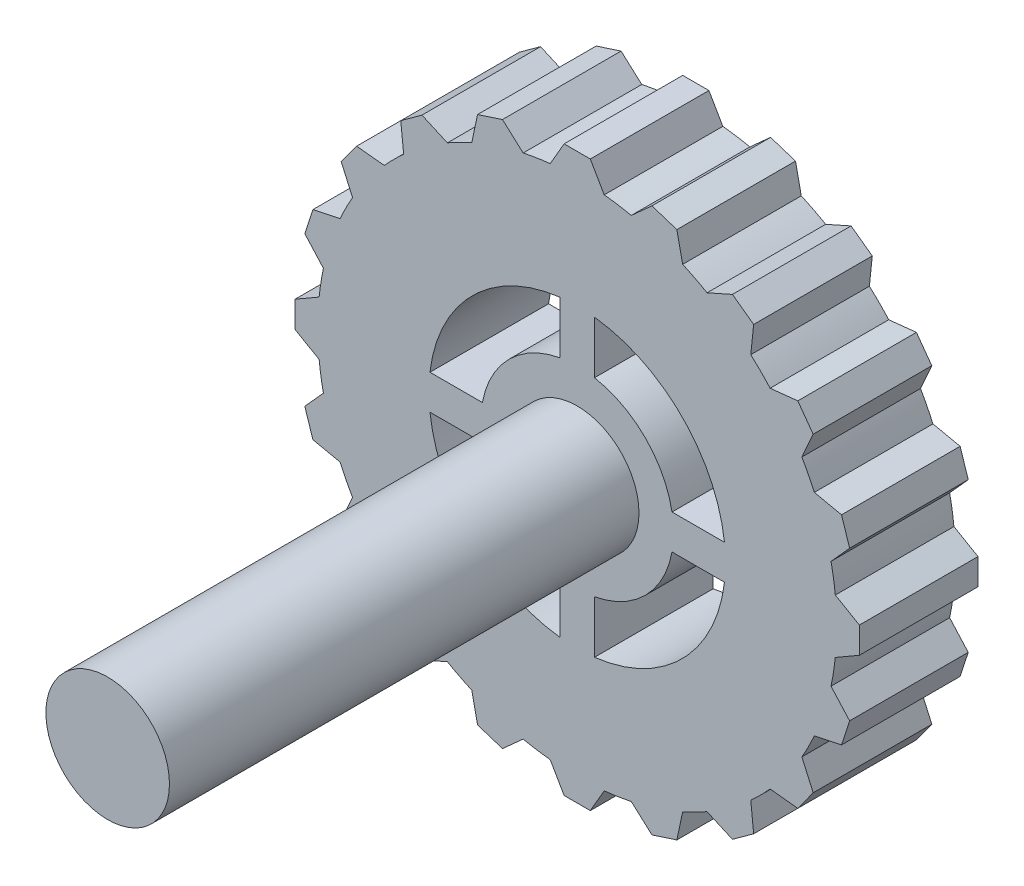
SolidWorks part; units mm, degrees
ref_plane "Płaszczyzna przednia" through (0, 0, 0) normal (0, 0, 1) x (1, 0, 0)
ref_plane "Płaszczyzna górna" through (0, 0, 0) normal (0, 1, 0) x (1, 0, 0)
ref_plane "Płaszczyzna prawa" through (0, 0, 0) normal (1, 0, 0) x (0, 0, -1)
sketch "Szkic1" plane through (0, 0, 0) normal (0, 0, 1) x (1, 0, 0)
  line L0 (0, 0) -> (0, 1.25) construction
  line L1 (0, 0) -> (-4.6726, 0) construction
  line L8 (-2.9795, 0.35) -> (-1.9183, 0.35)
  line L9 (-2.9795, -0.35) -> (-1.9183, -0.35)
  line L10 (-0.35, 2.9795) -> (-0.35, 1.9183)
  line L11 (0.35, 2.9795) -> (0.35, 1.9183)
  line L12 (1.9183, 0.35) -> (2.9795, 0.35)
  line L13 (1.9183, -0.35) -> (2.9795, -0.35)
  line L14 (-0.35, -1.9183) -> (-0.35, -2.9795)
  line L15 (0.35, -2.9795) -> (0.35, -1.9183)
  line L16 (0, 2.8529) -> (0, 9.5556) construction
  line L17 (1.5121, 5.5115) -> (1.0938, 5.1348)
  line L18 (-0.265, 5.709) -> (-0.5465, 5.2215)
  line L22 (0.5465, 5.2215) -> (0.265, 5.709)
  line L23 (0.265, 5.709) -> (-0.265, 5.709)
  line L24 (0, 4.791) -> (0.265, 4.791) [skipped]
  line L25 (0.5154, 5.2246) -> (0.53, 5.25) [skipped]
  line L26 (-0.53, 5.25) -> (-0.5154, 5.2246) [skipped]
  line L27 (2.1332, 4.7971) -> (2.0162, 5.3477)
  line L28 (2.0162, 5.3477) -> (1.5121, 5.5115)
  line L29 (3.1413, 4.7744) -> (2.627, 4.5455)
  line L30 (3.5112, 3.9031) -> (3.5701, 4.4629)
  line L31 (3.5701, 4.4629) -> (3.1413, 4.7744)
  line L32 (4.4629, 3.5701) -> (3.9031, 3.5112)
  line L33 (4.5455, 2.627) -> (4.7744, 3.1413)
  line L34 (4.7744, 3.1413) -> (4.4629, 3.5701)
  line L35 (5.3477, 2.0162) -> (4.7971, 2.1332)
  line L36 (5.1348, 1.0938) -> (5.5115, 1.5121)
  line L37 (5.5115, 1.5121) -> (5.3477, 2.0162)
  line L38 (5.709, 0.265) -> (5.2215, 0.5465)
  line L39 (5.2215, -0.5465) -> (5.709, -0.265)
  line L40 (5.709, -0.265) -> (5.709, 0.265)
  line L41 (5.5115, -1.5121) -> (5.1348, -1.0938)
  line L42 (4.7971, -2.1332) -> (5.3477, -2.0162)
  line L43 (5.3477, -2.0162) -> (5.5115, -1.5121)
  line L44 (4.7744, -3.1413) -> (4.5455, -2.627)
  line L45 (3.9031, -3.5112) -> (4.4629, -3.5701)
  line L46 (4.4629, -3.5701) -> (4.7744, -3.1413)
  line L47 (3.5701, -4.4629) -> (3.5112, -3.9031)
  line L48 (2.627, -4.5455) -> (3.1413, -4.7744)
  line L49 (3.1413, -4.7744) -> (3.5701, -4.4629)
  line L50 (2.0162, -5.3477) -> (2.1332, -4.7971)
  line L51 (1.0938, -5.1348) -> (1.5121, -5.5115)
  line L52 (1.5121, -5.5115) -> (2.0162, -5.3477)
  line L53 (0.265, -5.709) -> (0.5465, -5.2215)
  line L54 (-0.5465, -5.2215) -> (-0.265, -5.709)
  line L55 (-0.265, -5.709) -> (0.265, -5.709)
  line L56 (-1.5121, -5.5115) -> (-1.0938, -5.1348)
  line L57 (-2.1332, -4.7971) -> (-2.0162, -5.3477)
  line L58 (-2.0162, -5.3477) -> (-1.5121, -5.5115)
  line L59 (-3.1413, -4.7744) -> (-2.627, -4.5455)
  line L60 (-3.5112, -3.9031) -> (-3.5701, -4.4629)
  line L61 (-3.5701, -4.4629) -> (-3.1413, -4.7744)
  line L62 (-4.4629, -3.5701) -> (-3.9031, -3.5112)
  line L63 (-4.5455, -2.627) -> (-4.7744, -3.1413)
  line L64 (-4.7744, -3.1413) -> (-4.4629, -3.5701)
  line L65 (-5.3477, -2.0162) -> (-4.7971, -2.1332)
  line L66 (-5.1348, -1.0938) -> (-5.5115, -1.5121)
  line L67 (-5.5115, -1.5121) -> (-5.3477, -2.0162)
  line L68 (-5.709, -0.265) -> (-5.2215, -0.5465)
  line L69 (-5.2215, 0.5465) -> (-5.709, 0.265)
  line L70 (-5.709, 0.265) -> (-5.709, -0.265)
  line L71 (-5.5115, 1.5121) -> (-5.1348, 1.0938)
  line L72 (-4.7971, 2.1332) -> (-5.3477, 2.0162)
  line L73 (-5.3477, 2.0162) -> (-5.5115, 1.5121)
  line L74 (-4.7744, 3.1413) -> (-4.5455, 2.627)
  line L75 (-3.9031, 3.5112) -> (-4.4629, 3.5701)
  line L76 (-4.4629, 3.5701) -> (-4.7744, 3.1413)
  line L77 (-3.5701, 4.4629) -> (-3.5112, 3.9031)
  line L78 (-2.627, 4.5455) -> (-3.1413, 4.7744)
  line L79 (-3.1413, 4.7744) -> (-3.5701, 4.4629)
  line L80 (-2.0162, 5.3477) -> (-2.1332, 4.7971)
  line L81 (-1.0938, 5.1348) -> (-1.5121, 5.5115)
  line L82 (-1.5121, 5.5115) -> (-2.0162, 5.3477)
  circle A0 centre (0, 0) radius 1.25
  arc A1 (-0.5465, 5.2215) -> (0.5465, 5.2215) centre (0, 0) ccw
  arc A2 (-1.9183, -0.35) -> (-0.35, -1.9183) centre (0, 0) ccw
  arc A3 (-2.9795, -0.35) -> (-0.35, -2.9795) centre (0, 0) ccw
  arc A4 (0.35, -1.9183) -> (1.9183, -0.35) centre (0, 0) ccw
  arc A5 (0.35, -2.9795) -> (2.9795, -0.35) centre (0, 0) ccw
  arc A6 (1.9183, 0.35) -> (0.35, 1.9183) centre (0, 0) ccw
  arc A7 (2.9795, 0.35) -> (0.35, 2.9795) centre (0, 0) ccw
  arc A8 (-0.35, 1.9183) -> (-1.9183, 0.35) centre (0, 0) ccw
  arc A9 (-0.35, 2.9795) -> (-2.9795, 0.35) centre (0, 0) ccw
  arc A10 (1.0938, 5.1348) -> (2.1332, 4.7971) centre (0, 0) ccw
  arc A11 (2.627, 4.5455) -> (3.5112, 3.9031) centre (0, 0) ccw
  arc A12 (3.9031, 3.5112) -> (4.5455, 2.627) centre (0, 0) ccw
  arc A13 (4.7971, 2.1332) -> (5.1348, 1.0938) centre (0, 0) ccw
  arc A14 (5.2215, 0.5465) -> (5.2215, -0.5465) centre (0, 0) ccw
  arc A15 (5.1348, -1.0938) -> (4.7971, -2.1332) centre (0, 0) ccw
  arc A16 (4.5455, -2.627) -> (3.9031, -3.5112) centre (0, 0) ccw
  arc A17 (3.5112, -3.9031) -> (2.627, -4.5455) centre (0, 0) ccw
  arc A18 (2.1332, -4.7971) -> (1.0938, -5.1348) centre (0, 0) ccw
  arc A19 (0.5465, -5.2215) -> (-0.5465, -5.2215) centre (0, 0) ccw
  arc A20 (-1.0938, -5.1348) -> (-2.1332, -4.7971) centre (0, 0) ccw
  arc A21 (-2.627, -4.5455) -> (-3.5112, -3.9031) centre (0, 0) ccw
  arc A22 (-3.9031, -3.5112) -> (-4.5455, -2.627) centre (0, 0) ccw
  arc A23 (-4.7971, -2.1332) -> (-5.1348, -1.0938) centre (0, 0) ccw
  arc A24 (-5.2215, -0.5465) -> (-5.2215, 0.5465) centre (0, 0) ccw
  arc A25 (-5.1348, 1.0938) -> (-4.7971, 2.1332) centre (0, 0) ccw
  arc A26 (-4.5455, 2.627) -> (-3.9031, 3.5112) centre (0, 0) ccw
  arc A27 (-3.5112, 3.9031) -> (-2.627, 4.5455) centre (0, 0) ccw
  arc A28 (-2.1332, 4.7971) -> (-1.0938, 5.1348) centre (0, 0) ccw
  point P112 (0, 0)
  dimension "D1" = 2.5
  dimension "D2" = 10.5
  dimension "D3" = 0.35
  dimension "D4" = 0.35
  dimension "D7" = 20
  dimension "D5" = 0.35
  dimension "D6" = 0.35
extrude "Dodanie-wyciągnięcie2" add sketch "Szkic1" along normal blind 2.4 contours A1 A10 A9 L10 A8 L8 A7 L12 A6 L11 | A1 L69 L70 L68 | A10 L22 L23 L18 | A1 L33 L34 L32 | A1 L36 L37 L35 | A1 L39 L40 L38 | A1 L42 L43 L41 | A1 L45 L46 L44 | A1 L48 L49 L47 | A1 L51 L52 L50 | L73 L71 A25 L72 | L62 A22 L63 L64 | L66 L67 L65 A23 | L78 L79 L77 A27 | L82 L80 A28 L81 | L75 L76 L74 A26 | L60 L61 L59 A21 | L57 L58 L56 A20 | L54 L55 L53 A19 | L29 A11 L30 L31
sketch "Szkic2" plane through (0, 0, 0) normal (0, 0, -1) x (-1, 0, 0)
  circle A0 centre (0, 0) radius 2.3387
  circle A1 centre (0, 0) radius 1.25
  circle A2 centre (0, 0) radius 3.6476
extrude "Dodanie-wyciągnięcie3" add sketch "Szkic2" along normal blind 2 contours A1
sketch "Szkic3" plane through (0, 0, 2.4) normal (0, 0, 1) x (1, 0, 0)
  circle A0 centre (0, 0) radius 1.25
extrude "Dodanie-wyciągnięcie4" add sketch "Szkic3" along normal blind 9.5 contours A0
sketch "Szkic4" plane through (0, 0, 0) normal (0, 0, -1) x (-1, 0, 0)
  line L0 (0, 0) -> (-8.9414, 0) construction
  line L1 (0, 0) -> (0, 6.5108) construction
  line L2 (-2.9795, 0.35) -> (-1.9183, 0.35)
  line L3 (-2.9795, -0.35) -> (-1.9183, -0.35)
  line L4 (1.9183, 0.35) -> (2.9795, 0.35)
  line L5 (1.9183, -0.35) -> (2.9795, -0.35)
  line L6 (-0.35, 2.9795) -> (-0.35, 1.9183)
  line L7 (0.35, 2.9795) -> (0.35, 1.9183)
  line L8 (-0.35, -1.9183) -> (-0.35, -2.9795)
  line L9 (0.35, -1.9183) -> (0.35, -2.9795)
  arc A0 (-2.9795, -0.35) -> (-0.35, -2.9795) centre (0, 0) ccw
  arc A1 (-1.9183, -0.35) -> (-0.35, -1.9183) centre (0, 0) ccw
  arc A2 (1.9183, 0.35) -> (0.35, 1.9183) centre (0, 0) ccw
  arc A3 (2.9795, 0.35) -> (0.35, 2.9795) centre (0, 0) ccw
  arc A4 (-0.35, 2.9795) -> (-2.9795, 0.35) centre (0, 0) ccw
  arc A5 (-0.35, 1.9183) -> (-1.9183, 0.35) centre (0, 0) ccw
  arc A6 (0.35, -1.9183) -> (1.9183, -0.35) centre (0, 0) ccw
  arc A7 (0.35, -2.9795) -> (2.9795, -0.35) centre (0, 0) ccw
  dimension "D1" = 6
  dimension "D2" = 3.9
  dimension "D3" = 0.35
  dimension "D4" = 0.35
  dimension "D5" = 0.35
  dimension "D6" = 0.35
extrude "Wytnij-wyciągnięcie1" cut sketch "Szkic4" against normal blind 9.5
